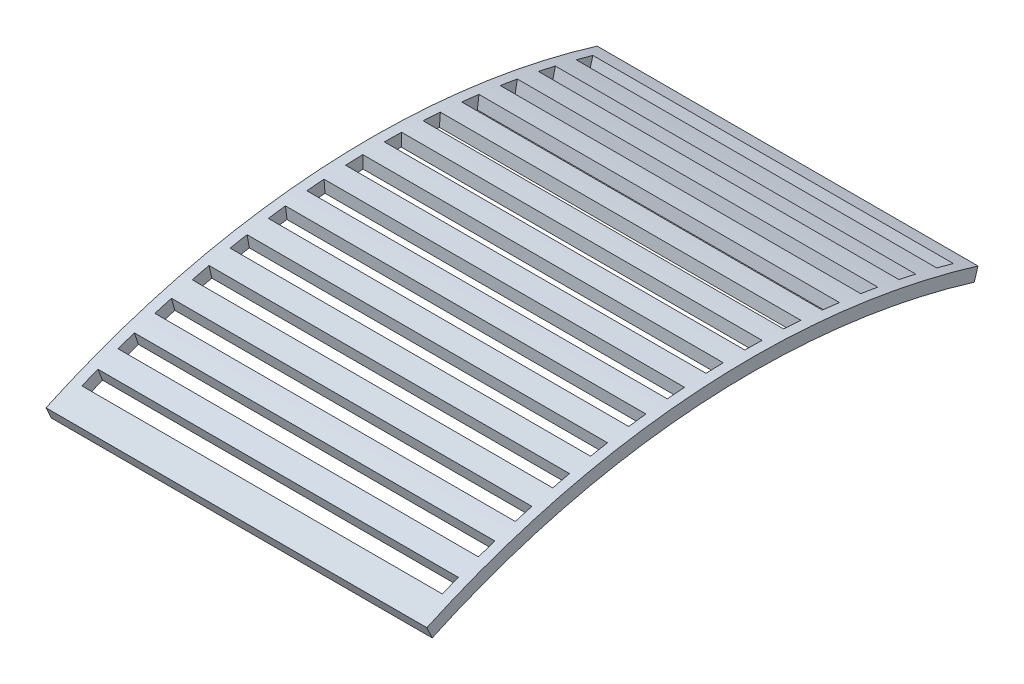
SolidWorks part; units mm, degrees
ref_plane "Front Plane" through (0, 0, 0) normal (0, 0, 1) x (1, 0, 0)
ref_plane "Top Plane" through (0, 0, 0) normal (0, 1, 0) x (1, 0, 0)
ref_plane "Right Plane" through (0, 0, 0) normal (1, 0, 0) x (0, 0, -1)
sketch "Sketch1" plane through (0, 0, 0) normal (1, 0, 0) x (0, 0, -1)
  circle A2 centre (0, -8.2378) radius 178
sketch "Sketch2" plane through (0, 0, 0) normal (1, 0, 0) x (0, 0, -1)
  circle A0 centre (0, -8.2378) radius 178
extrude "Extrude-Thin1" add sketch "Sketch2" along normal blind 90 thin
ref_plane "Plane1" through (0, 171.7622, 0) normal (0, 1, 0) x (1, 0, 0)
sketch "Sketch3" plane through (0, 171.7622, 0) normal (0, 1, 0) x (1, 0, 0)
  line L0 (2.5139, -58.2963) -> (87.5139, -58.2963)
  line L1 (0.0906, 53.2073) -> (89.9006, 53.2073)
  line L2 (0.0906, 53.2073) -> (0.0906, -77.7927)
  line L3 (0.0906, -77.7927) -> (89.9006, -77.7927)
  line L4 (89.9006, 53.2073) -> (89.9006, -77.7927)
  line L5 (2.5139, -71.2963) -> (87.5139, -71.2963)
  line L6 (2.5139, -71.2963) -> (2.5139, -67.2963)
  line L7 (2.5139, -67.2963) -> (87.5139, -67.2963)
  line L8 (87.5139, -71.2963) -> (87.5139, -67.2963)
  line L9 (2.5139, -62.2963) -> (2.5139, -58.2963)
  line L10 (2.5139, -62.2963) -> (87.5139, -62.2963)
  line L11 (87.5139, -62.2963) -> (87.5139, -58.2963)
  line L12 (2.5139, -49.2963) -> (87.5139, -49.2963)
  line L13 (2.5139, -53.2963) -> (2.5139, -49.2963)
  line L14 (2.5139, -53.2963) -> (87.5139, -53.2963)
  line L15 (87.5139, -53.2963) -> (87.5139, -49.2963)
  line L16 (2.5139, -40.2963) -> (87.5139, -40.2963)
  line L17 (2.5139, -44.2963) -> (2.5139, -40.2963)
  line L18 (2.5139, -44.2963) -> (87.5139, -44.2963)
  line L19 (87.5139, -44.2963) -> (87.5139, -40.2963)
  line L20 (2.5139, -31.2963) -> (87.5139, -31.2963)
  line L21 (2.5139, -35.2963) -> (2.5139, -31.2963)
  line L22 (2.5139, -35.2963) -> (87.5139, -35.2963)
  line L23 (87.5139, -35.2963) -> (87.5139, -31.2963)
  line L24 (2.5139, -22.2963) -> (87.5139, -22.2963)
  line L25 (2.5139, -26.2963) -> (2.5139, -22.2963)
  line L26 (2.5139, -26.2963) -> (87.5139, -26.2963)
  line L27 (87.5139, -26.2963) -> (87.5139, -22.2963)
  line L28 (2.5139, -13.2963) -> (87.5139, -13.2963)
  line L29 (2.5139, -17.2963) -> (2.5139, -13.2963)
  line L30 (2.5139, -17.2963) -> (87.5139, -17.2963)
  line L31 (87.5139, -17.2963) -> (87.5139, -13.2963)
  line L32 (2.5139, -4.2963) -> (87.5139, -4.2963)
  line L33 (2.5139, -8.2963) -> (2.5139, -4.2963)
  line L34 (2.5139, -8.2963) -> (87.5139, -8.2963)
  line L35 (87.5139, -8.2963) -> (87.5139, -4.2963)
  line L36 (2.5139, 4.7037) -> (87.5139, 4.7037)
  line L37 (2.5139, 0.7037) -> (2.5139, 4.7037)
  line L38 (2.5139, 0.7037) -> (87.5139, 0.7037)
  line L39 (87.5139, 0.7037) -> (87.5139, 4.7037)
  line L40 (2.5139, 13.7037) -> (87.5139, 13.7037)
  line L41 (2.5139, 9.7037) -> (2.5139, 13.7037)
  line L42 (2.5139, 9.7037) -> (87.5139, 9.7037)
  line L43 (87.5139, 9.7037) -> (87.5139, 13.7037)
  line L44 (2.5139, 22.7037) -> (87.5139, 22.7037)
  line L45 (2.5139, 18.7037) -> (2.5139, 22.7037)
  line L46 (2.5139, 18.7037) -> (87.5139, 18.7037)
  line L47 (87.5139, 18.7037) -> (87.5139, 22.7037)
  line L48 (2.5139, 31.7037) -> (87.5139, 31.7037)
  line L49 (2.5139, 27.7037) -> (2.5139, 31.7037)
  line L50 (2.5139, 27.7037) -> (87.5139, 27.7037)
  line L51 (87.5139, 27.7037) -> (87.5139, 31.7037)
  line L52 (2.5139, 40.7037) -> (87.5139, 40.7037)
  line L53 (2.5139, 36.7037) -> (2.5139, 40.7037)
  line L54 (2.5139, 36.7037) -> (87.5139, 36.7037)
  line L55 (87.5139, 36.7037) -> (87.5139, 40.7037)
  line L56 (2.5139, 49.7037) -> (87.5139, 49.7037)
  line L57 (2.5139, 45.7037) -> (2.5139, 49.7037)
  line L58 (2.5139, 45.7037) -> (87.5139, 45.7037)
  line L59 (87.5139, 45.7037) -> (87.5139, 49.7037)
  dimension "D1" = 131
  dimension "D2" = 89.81
  dimension "D3" = 85
  dimension "D4" = 4
  dimension "D5" = 14
wrap "Wrap1" sketch "Sketch3" wrap type emboss source sketch "Sketch3" thickness 3 face at (90, -8.2378, -180) parameters "D1"=3
sketch "Sketch5" plane through (0, 0, 0) normal (1, 0, 0) x (0, 0, -1)
  circle A0 centre (0, -8.2378) radius 180
extrude "Cut-Extrude1" cut sketch "Sketch5" along normal blind 119
